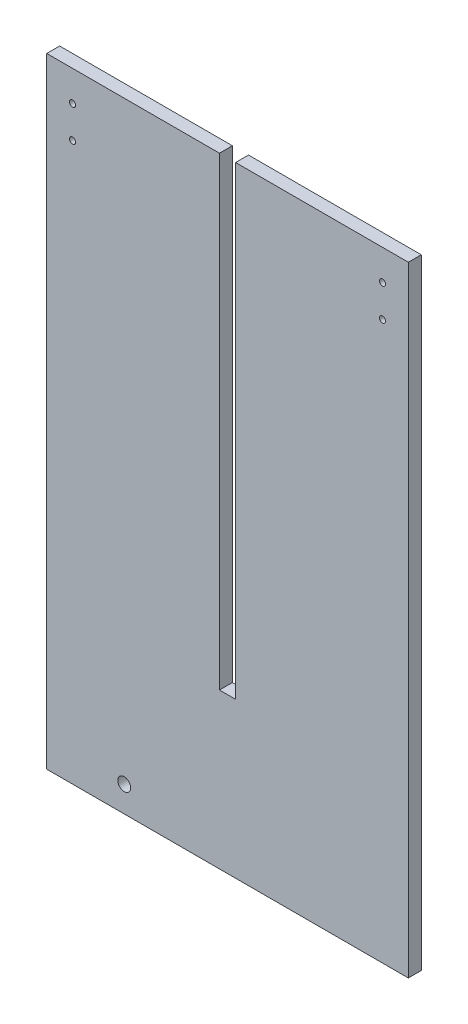
SolidWorks part; units mm, degrees
ref_plane "Front Plane" through (0, 0, 0) normal (0, 0, 1) x (1, 0, 0)
ref_plane "Top Plane" through (0, 0, 0) normal (0, 1, 0) x (1, 0, 0)
ref_plane "Right Plane" through (0, 0, 0) normal (1, 0, 0) x (0, 0, -1)
sketch "Sketch2" plane through (0, 0, 0) normal (0, 0, 1) x (1, 0, 0)
  line L0 (0, 152.4) -> (0, -152.4) construction
  line L1 (-88.9, 152.4) -> (88.9, 152.4)
  line L2 (-88.9, 152.4) -> (-88.9, -152.4)
  line L3 (-88.9, -152.4) -> (88.9, -152.4)
  line L4 (88.9, 152.4) -> (88.9, -152.4)
  line L5 (-88.9, 107.95) -> (-88.9, 63.5)
  line L6 (-88.9, 152.4) -> (-95.25, 152.4)
  line L7 (-88.9, 152.4) -> (-88.9, 107.95)
  line L8 (-88.9, 107.95) -> (-95.25, 107.95)
  line L9 (-95.25, 152.4) -> (-95.25, 107.95)
  line L10 (88.9, 152.4) -> (95.25, 152.4)
  line L11 (88.9, 152.4) -> (88.9, 107.95)
  line L12 (88.9, 107.95) -> (95.25, 107.95)
  line L13 (95.25, 152.4) -> (95.25, 107.95)
  line L14 (-68.0357, -152.4) -> (-95.25, -152.4)
  line L15 (-68.0357, -152.4) -> (-68.0357, -158.75)
  line L16 (-68.0357, -158.75) -> (-95.25, -158.75)
  line L17 (-95.25, -152.4) -> (-95.25, -158.75)
  line L18 (-88.9, 107.95) -> (-95.25, 107.95)
  line L19 (-95.25, 107.95) -> (-95.25, 63.5)
  line L20 (-88.9, 63.5) -> (-95.25, 63.5)
  line L21 (88.9, 107.95) -> (88.9, 63.5)
  line L22 (88.9, 107.95) -> (95.25, 107.95)
  line L23 (95.25, 107.95) -> (95.25, 63.5)
  line L24 (88.9, 63.5) -> (95.25, 63.5)
  line L25 (-88.9, 63.5) -> (-88.9, 19.05)
  line L26 (-88.9, 63.5) -> (-95.25, 63.5)
  line L27 (-95.25, 63.5) -> (-95.25, 19.05)
  line L28 (-88.9, 19.05) -> (-95.25, 19.05)
  line L29 (88.9, 63.5) -> (88.9, 19.05)
  line L30 (88.9, 63.5) -> (95.25, 63.5)
  line L31 (95.25, 63.5) -> (95.25, 19.05)
  line L32 (88.9, 19.05) -> (95.25, 19.05)
  line L33 (-88.9, 19.05) -> (-88.9, -25.4)
  line L34 (-88.9, 19.05) -> (-95.25, 19.05)
  line L35 (-95.25, 19.05) -> (-95.25, -25.4)
  line L36 (-88.9, -25.4) -> (-95.25, -25.4)
  line L37 (88.9, 19.05) -> (88.9, -25.4)
  line L38 (88.9, 19.05) -> (95.25, 19.05)
  line L39 (95.25, 19.05) -> (95.25, -25.4)
  line L40 (88.9, -25.4) -> (95.25, -25.4)
  line L41 (-88.9, -25.4) -> (-88.9, -69.85)
  line L42 (-88.9, -25.4) -> (-95.25, -25.4)
  line L43 (-95.25, -25.4) -> (-95.25, -69.85)
  line L44 (-88.9, -69.85) -> (-95.25, -69.85)
  line L45 (88.9, -25.4) -> (88.9, -69.85)
  line L46 (88.9, -25.4) -> (95.25, -25.4)
  line L47 (95.25, -25.4) -> (95.25, -69.85)
  line L48 (88.9, -69.85) -> (95.25, -69.85)
  line L49 (-88.9, -69.85) -> (-88.9, -114.3)
  line L50 (-88.9, -69.85) -> (-95.25, -69.85)
  line L51 (-95.25, -69.85) -> (-95.25, -114.3)
  line L52 (-88.9, -114.3) -> (-95.25, -114.3)
  line L53 (88.9, -69.85) -> (88.9, -114.3)
  line L54 (88.9, -69.85) -> (95.25, -69.85)
  line L55 (95.25, -69.85) -> (95.25, -114.3)
  line L56 (88.9, -114.3) -> (95.25, -114.3)
  line L57 (-88.9, -114.3) -> (-88.9, -158.75)
  line L58 (-88.9, -114.3) -> (-95.25, -114.3)
  line L59 (-95.25, -114.3) -> (-95.25, -158.75)
  line L60 (-88.9, -158.75) -> (-95.25, -158.75)
  line L61 (88.9, -114.3) -> (88.9, -158.75)
  line L62 (88.9, -114.3) -> (95.25, -114.3)
  line L63 (95.25, -114.3) -> (95.25, -158.75)
  line L64 (88.9, -158.75) -> (95.25, -158.75)
  line L65 (-40.8214, -152.4) -> (-40.8214, -158.75)
  line L66 (-40.8214, -152.4) -> (-68.0357, -152.4)
  line L67 (-68.0357, -152.4) -> (-68.0357, -158.75)
  line L68 (-40.8214, -158.75) -> (-68.0357, -158.75)
  line L69 (-13.6071, -152.4) -> (-13.6071, -158.75)
  line L70 (-13.6071, -152.4) -> (-40.8214, -152.4)
  line L71 (-40.8214, -152.4) -> (-40.8214, -158.75)
  line L72 (-13.6071, -158.75) -> (-40.8214, -158.75)
  line L73 (13.6071, -152.4) -> (13.6071, -158.75)
  line L74 (13.6071, -152.4) -> (-13.6071, -152.4)
  line L75 (-13.6071, -152.4) -> (-13.6071, -158.75)
  line L76 (13.6071, -158.75) -> (-13.6071, -158.75)
  line L77 (40.8214, -152.4) -> (40.8214, -158.75)
  line L78 (40.8214, -152.4) -> (13.6071, -152.4)
  line L79 (13.6071, -152.4) -> (13.6071, -158.75)
  line L80 (40.8214, -158.75) -> (13.6071, -158.75)
  line L81 (68.0357, -152.4) -> (68.0357, -158.75)
  line L82 (68.0357, -152.4) -> (40.8214, -152.4)
  line L83 (40.8214, -152.4) -> (40.8214, -158.75)
  line L84 (68.0357, -158.75) -> (40.8214, -158.75)
  line L85 (95.25, -152.4) -> (95.25, -158.75)
  line L86 (95.25, -152.4) -> (68.0357, -152.4)
  line L87 (68.0357, -152.4) -> (68.0357, -158.75)
  line L88 (95.25, -158.75) -> (68.0357, -158.75)
  point P6 (0, 0)
  dimension "D1" = 177.8
  dimension "D2" = 190.5
  dimension "D3" = 304.8
  dimension "D4" = 311.15
  dimension "D6" = 44.45
  dimension "D8" = 27.2143
  dimension "D5" = 7
  dimension "D7" = 7
extrude "Boss-Extrude1" add sketch "Sketch2" along normal blind 6.35 contours L0 L1 L2 L3 | L1 L0 L3 L4 | L20 L2 L8 L19 | L36 L2 L28 L35 | L52 L2 L44 L51 | L3 L57 L16 L15 | L72 L69 L3 L65 | L80 L77 L3 L73 | L4 L56 L55 L48 | L4 L40 L39 L32 | L4 L24 L23 L12 | L88 L61 L3 L81
sketch "Sketch3" plane through (0, 0, 6.35) normal (0, 0, 1) x (1, 0, 0)
  line L0 (-88.9, 152.4) -> (88.9, 152.4) construction
  line L1 (-3.9688, 152.4) -> (3.9687, 152.4)
  line L2 (-3.9688, 152.4) -> (-3.9687, -76.2)
  line L3 (-3.9687, -76.2) -> (3.9688, -76.2)
  line L4 (3.9687, 152.4) -> (3.9688, -76.2)
  line L5 (0, -76.2) -> (0, 0) construction
  dimension "D1" = 7.9375
  dimension "D2" = 228.6
extrude "Cut-Extrude1" cut sketch "Sketch3" against normal through all
sketch "Sketch4" plane through (0, 0, 6.35) normal (0, 0, 1) x (1, 0, 0)
  line L0 (-68.0357, -152.4) -> (-40.8214, -152.4) construction
  line L1 (-88.9, -114.3) -> (-88.9, -158.75) construction
  circle A0 centre (-50.8, -139.7) radius 3.175
  dimension "D1" = 6.35
  dimension "D2" = 12.7
  dimension "D3" = 38.1
extrude "Cut-Extrude2" cut sketch "Sketch4" against normal through all
sketch "Sketch5" plane through (0, 0, 6.35) normal (0, 0, 1) x (1, 0, 0)
  line L0 (0, -152.4) -> (0, 152.4) construction
  line L1 (-13.6071, -152.4) -> (13.6071, -152.4) construction
  line L2 (3.9687, 152.4) -> (88.9, 152.4) construction
  line L3 (-88.9, 152.4) -> (-3.9688, 152.4) construction
  line L5 (-95.25, 107.95) -> (-95.25, 63.5) construction
  circle A0 centre (-76.2, 137.4) radius 1.5
  circle A1 centre (-76.2, 121.65) radius 1.5
  circle A2 centre (76.2, 121.65) radius 1.5
  circle A3 centre (76.2, 137.4) radius 1.5
  dimension "D1" = 15.75
  dimension "D2" = 15
  dimension "D4" = 3
  dimension "D5" = 3
  dimension "D3" = 19.05
extrude "Cut-Extrude3" cut sketch "Sketch5" against normal up to surface (6.35 mm away) up to face at (-47.625, -139.7, 0)
sketch "Sketch6" plane through (0, 0, 6.35) normal (0, 0, 1) x (1, 0, 0)
  line L1 (-95.25, 63.5) -> (-88.9, 63.5)
  line L2 (-95.25, 63.5) -> (-95.25, 19.05)
  line L3 (-95.25, 19.05) -> (-88.9, 19.05)
  line L4 (-88.9, 63.5) -> (-88.9, 19.05)
  line L5 (-95.25, -25.4) -> (-88.9, -25.4)
  line L6 (-95.25, -25.4) -> (-95.25, -69.85)
  line L7 (-95.25, -69.85) -> (-88.9, -69.85)
  line L8 (-88.9, -25.4) -> (-88.9, -69.85)
  line L9 (95.25, 63.5) -> (88.9, 63.5)
  line L10 (95.25, 63.5) -> (95.25, 19.05)
  line L11 (95.25, 19.05) -> (88.9, 19.05)
  line L12 (88.9, 63.5) -> (88.9, 19.05)
  line L13 (88.9, -25.4) -> (95.25, -25.4)
  line L14 (88.9, -25.4) -> (88.9, -69.85)
  line L15 (88.9, -69.85) -> (95.25, -69.85)
  line L16 (95.25, -25.4) -> (95.25, -69.85)
extrude "Boss-Extrude2" add sketch "Sketch6" against normal up to surface (6.35 mm away) up to face at (77.7, 137.4, 0)
sketch "Sketch7" plane through (0, 0, 6.35) normal (0, 0, 1) x (1, 0, 0)
  line L1 (-40.8214, -152.4) -> (-13.6071, -152.4)
  line L2 (-40.8214, -152.4) -> (-40.8214, -158.75)
  line L3 (-40.8214, -158.75) -> (-13.6071, -158.75)
  line L4 (-13.6071, -152.4) -> (-13.6071, -158.75)
  line L5 (13.6071, -152.4) -> (40.8214, -152.4)
  line L6 (13.6071, -152.4) -> (13.6071, -158.75)
  line L7 (13.6071, -158.75) -> (40.8214, -158.75)
  line L8 (40.8214, -152.4) -> (40.8214, -158.75)
extrude "Cut-Extrude4" cut sketch "Sketch7" against normal up to surface (6.35 mm away) up to face at (0, -62.5929, 0)
sketch "Sketch9" plane through (0, 0, 0) normal (0, 0, -1) x (-1, 0, 0)
  line L0 (-88.9, 107.95) -> (-88.9, -114.3)
  line L1 (-88.9, -114.3) -> (-95.25, -114.3)
  line L2 (-95.25, -114.3) -> (-95.25, 107.95)
  line L3 (-95.25, 107.95) -> (-88.9, 107.95)
  line L4 (88.9, 107.95) -> (88.9, -114.3)
  line L5 (88.9, -114.3) -> (95.25, -114.3)
  line L6 (95.25, -114.3) -> (95.25, 107.95)
  line L7 (95.25, 107.95) -> (88.9, 107.95)
  line L9 (-68.0357, -152.4) -> (-88.9, -152.4)
  line L10 (-68.0357, -152.4) -> (-68.0357, -158.75)
  line L11 (-68.0357, -158.75) -> (-88.9, -158.75)
  line L12 (-88.9, -152.4) -> (-88.9, -158.75)
  line L13 (68.0357, -152.4) -> (88.9, -152.4)
  line L14 (68.0357, -152.4) -> (68.0357, -158.75)
  line L15 (68.0357, -158.75) -> (88.9, -158.75)
  line L16 (88.9, -152.4) -> (88.9, -158.75)
extrude "Cut-Extrude5" cut sketch "Sketch9" against normal up to surface (6.35 mm away) up to face at (0, -25.4, 6.35)
equation "\"Height\"= 12in"
equation "\"Depth\"= 7in"
equation "\"WallThickness\"= 0.25in"
equation "\"FloorThickness\"= 0.25in"
equation "\"D1@Sketch2\"=\"Depth\""
equation "\"D2@Sketch2\"=\"D1@Sketch2\"+2*\"WallThickness\""
equation "\"D3@Sketch2\"=\"Height\""
equation "\"D4@Sketch2\"=\"D3@Sketch2\"+\"FloorThickness\""
equation "\"D6@Sketch2\"=\"D4@Sketch2\"/\"D5@Sketch2\""
equation "\"D8@Sketch2\"=\"D2@Sketch2\"/\"D7@Sketch2\""
equation "\"D1@Boss-Extrude1\"=\"WallThickness\""
equation "\"Width\" = 30in"
